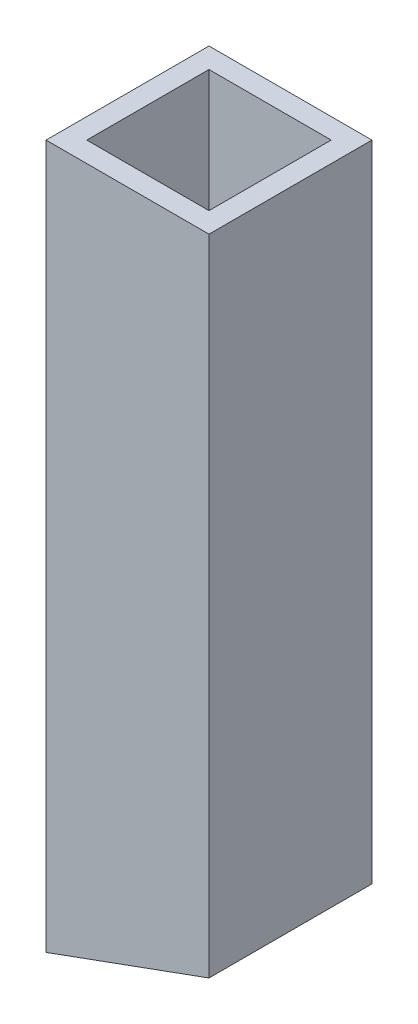
SolidWorks part; units mm, degrees
ref_plane "Front Plane" through (0, 0, 0) normal (0, 0, 1) x (1, 0, 0)
ref_plane "Top Plane" through (0, 0, 0) normal (0, 1, 0) x (1, 0, 0)
ref_plane "Right Plane" through (0, 0, 0) normal (1, 0, 0) x (0, 0, -1)
sketch "Sketch1" plane through (0, 0, 0) normal (0, 0, 1) x (1, 0, 0)
  line L0 (-12.7, -54.8321) -> (12.7, -45.5872)
  line L1 (-12.7, 54.8321) -> (12.7, 54.8321)
  line L2 (-12.7, 54.8321) -> (-12.7, -54.8321)
  line L4 (12.7, 54.8321) -> (12.7, -45.5872)
  line L5 (-12.7, 54.8321) -> (51.3901, -221.8761) construction
  line L6 (-12.7, -54.8321) -> (12.7, 54.8321) construction
  point P0 (0, 0)
  point P5 (0, 54.8321)
  dimension "D1" = 25.4
  dimension "D2" = 279.4
  dimension "D3" = 110
extrude "Boss-Extrude1" add sketch "Sketch1" along normal mid plane 25.4
sketch "Sketch2" plane through (0, 54.8321, 0) normal (0, 1, 0) x (1, 0, 0)
  line L8 (9.525, 9.525) -> (-9.525, 9.525)
  line L9 (-9.525, 9.525) -> (-9.525, -9.525)
  line L10 (-9.525, -9.525) -> (9.525, -9.525)
  line L11 (9.525, -9.525) -> (9.525, 9.525)
  line L12 (9.525, 9.525) -> (-9.525, 9.525)
  line L13 (-9.525, 9.525) -> (-9.525, -9.525)
  line L14 (-9.525, -9.525) -> (9.525, -9.525)
  line L15 (9.525, -9.525) -> (9.525, 9.525)
  dimension "D1" = 3.175
extrude "Cut-Extrude1" cut sketch "Sketch2" against normal through all
